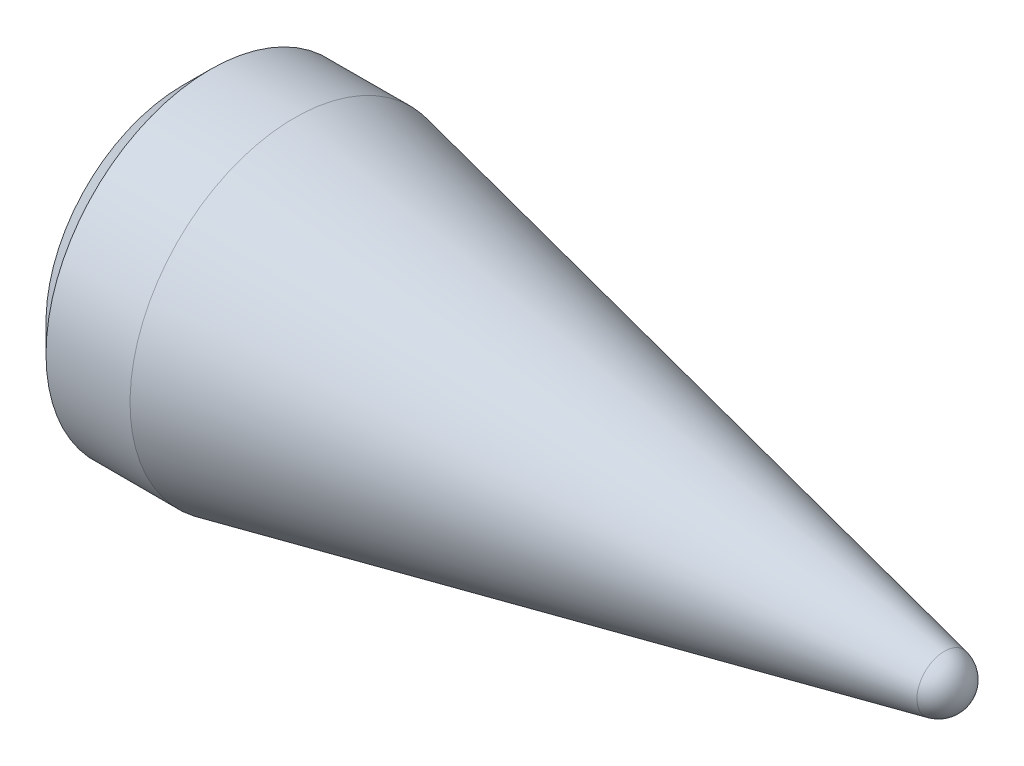
SolidWorks part; units mm, degrees
ref_plane "Front Plane" through (0, 0, 0) normal (0, 0, 1) x (1, 0, 0)
ref_plane "Top Plane" through (0, 0, 0) normal (0, 1, 0) x (1, 0, 0)
ref_plane "Right Plane" through (0, 0, 0) normal (1, 0, 0) x (0, 0, -1)
sketch "Sketch1" plane through (0, 0, 0) normal (0, 0, 1) x (1, 0, 0)
  line L0 (-11.1042, 0) -> (21.3198, 0) construction
  line L1 (0, 0) -> (0, 12.7) construction
  line L2 (45.477, 3.1066) -> (-28.2034, 18.6495)
  line L3 (25.4, 7.3419) -> (25.4, 0) construction
  line L4 (-28.2034, 18.6495) -> (-28.2034, 0) construction
  line L5 (-28.2034, 18.6495) -> (-40.9034, 18.6495)
  line L6 (-40.9034, 18.6495) -> (-40.9034, 0)
  line L7 (-40.9034, 0) -> (47.9966, 0)
  arc A0 (45.477, 3.1066) -> (47.9966, 0) centre (44.8216, 0) cw
  dimension "D6" = 3.175
  dimension "D1" = 12.7
  dimension "D2" = 7.3419
  dimension "D3" = 76.2
  dimension "D4" = 25.4
  dimension "D5" = 12.7
revolve "Revolve1" add sketch "Sketch1" angle 360 about L7
chamfer "Chamfer1" distance 3.175 angle 45 1 edges at (-40.9034, -18.6495, 0)
